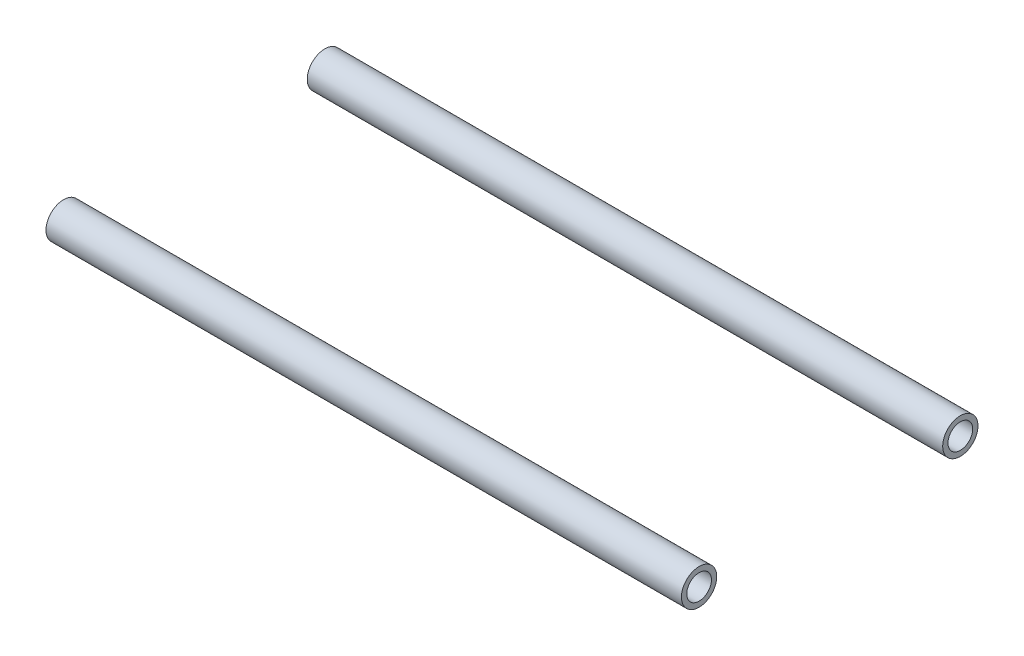
SolidWorks part; units mm, degrees
ref_plane "Front Plane" through (0, 0, 0) normal (0, 0, 1) x (1, 0, 0)
ref_plane "Top Plane" through (0, 0, 0) normal (0, 1, 0) x (1, 0, 0)
ref_plane "Right Plane" through (0, 0, 0) normal (1, 0, 0) x (0, 0, -1)
sketch "Sketch2" plane through (0, 0, 0) normal (0, 0, 1) x (1, 0, 0)
  line L0 (0, 0) -> (0, 2240) construction
  dimension "D1" = 2240
sketch "Sketch3" plane through (0, 0, 0) normal (0, 0, 1) x (1, 0, 0)
  line L0 (0, 1120) -> (2600, 1120) construction
  line L1 (0, 0) -> (0, 2240) construction
  line L2 (0, 1120) -> (1800, 1120) construction
  dimension "D1" = 2600
  dimension "D2" = 1800
ref_plane "Plane1" through (1800, 0, 0) normal (1, 0, 0) x (0, 0, -1)
ref_plane "Plane2" through (2600, 0, 0) normal (1, 0, 0) x (0, 0, -1)
sketch "Sketch6" plane through (2600, 0, 0) normal (1, 0, 0) x (0, 0, -1)
  line L0 (0, 1370) -> (0, 870) construction
  point P5 (0, 1120)
  dimension "D1" = 500
sketch "Sketch4" plane through (1800, 0, 0) normal (1, 0, 0) x (0, 0, -1)
  line L0 (0, 2240) -> (0, 0) construction
  line L1 (0, 0) -> (0, 2240) construction
  line L2 (370, 0) -> (-370, 0) construction
  line L3 (370, 2240) -> (-370, 2240) construction
  point P8 (0, 0)
  point P10 (0, 2240)
  dimension "D1" = 740
  dimension "D2" = 2240
sketch "Sketch5" plane through (0, 0, 0) normal (1, 0, 0) x (0, 0, -1)
  line L0 (-370, 2240) -> (370, 2240) construction
  line L2 (370, 0) -> (-370, 0) construction
  point P4 (0, 2240)
  point P9 (0, 0)
  dimension "D1" = 740
ref_plane "Plane3" through (0, 2240, 0) normal (0, -1, 0) x (-1, 0, 0)
ref_plane "Plane4" through (0, 0, 0) normal (0, 1, 0) x (1, 0, 0)
ref_plane "Plane5" through (458.1542, 0, 990.6037) normal (0.4198, 0, 0.9076) x (0.9076, 0, -0.4198)
ref_plane "Plane6" through (458.1542, 0, -990.6037) normal (-0.4198, 0, 0.9076) x (0.9076, 0, 0.4198)
sketch "Sketch7" plane through (0, 2240, 0) normal (0, -1, 0) x (-1, 0, 0)
  line L0 (-1800, -370) -> (0, -370)
  line L1 (-1800, 370) -> (-1800, -370) construction
  line L2 (0, -370) -> (0, 370) construction
  line L3 (0, 370) -> (0, -370) construction
  line L4 (-1800, 370) -> (0, 370)
  line L5 (-1800, 456.5) -> (-1800, -456.5) construction
sketch "Sketch8" plane through (0, 0, 0) normal (0, 1, 0) x (1, 0, 0)
  line L0 (1800, -370) -> (0, -370)
  line L1 (1800, 370) -> (0, 370)
sketch "Sketch9" plane through (458.1542, 0, -990.6037) normal (-0.4198, 0, 0.9076) x (0.9076, 0, 0.4198)
  line L0 (2359.8303, 870) -> (1478.411, 0)
  line L1 (2359.8303, 1370) -> (1478.411, 2240)
sketch "Sketch10" plane through (458.1542, 0, 990.6037) normal (0.4198, 0, 0.9076) x (0.9076, 0, -0.4198)
  line L0 (1478.411, 0) -> (2359.8303, 870)
  line L1 (1478.411, 2240) -> (2359.8303, 1370)
  line L2 (2359.8303, 870) -> (2359.8303, 1370)
sketch "Sketch11" plane through (0, 0, 0) normal (1, 0, 0) x (0, 0, -1)
  circle A0 centre (370, 2240) radius 50
  circle A1 centre (370, 2240) radius 35
  dimension "D1" = 100
  dimension "D2" = 15
sweep "MemberTL" add profiles "Sketch11" path "Sketch7"
sketch "Sketch12" plane through (0, 0, 0) normal (1, 0, 0) x (0, 0, -1)
  circle A0 centre (-370, 2240) radius 50
  circle A1 centre (-370, 2240) radius 35
  dimension "D1" = 100
  dimension "D2" = 15
sketch "Sketch13" plane through (0, 2240, 0) normal (0, -1, 0) x (-1, 0, 0)
  line L0 (0, -370) -> (-1800, -370)
sweep "MemberTR" add profiles "Sketch12" path "Sketch13"
equation "\"hatchHoleDiameter\"= 600mm"
equation "\"hullThickness\"= 120mm"
equation "\"gasketHullInterconnectWidth\"= 100mm"
equation "\"collarThickness\"= 20mm"
equation "\"hatchTunnelLength\"=200"
equation "\"oRingDiameter\"=2"
equation "\"boltPatternRadiusInterconnect\"=500"
equation "\"interconnectBoltDiameter\"=30"
equation "\"hatchShaftDiameter\"=20"
equation "\"hatchMinima\"=50"
equation "\"hullDiameter\"=2000"
equation "\"hatchMaxima\"=180"
equation "\"bushingFlatHatch\"=15"
equation "\"hingePivotDiameter\"=20"
equation "\"handleWidth\"=250"
equation "\"handleHeight\"=160"
equation "\"handleThickness\"=25"
equation "\"FrameLength\"= 2600"
equation "\"D1@Sketch2\"=\"hullDiameter\"+\"hullThickness\"*2"
equation "\"FrameMidLength\"= 1800"
equation "\"D1@Sketch3\"=\"FrameLength\""
equation "\"D2@Sketch3\"=\"FrameMidLength\""
equation "\"D1@Sketch4\"=\"hatchHoleDiameter\"+\"collarThickness\" * 2 + \"TubeOD\""
equation "\"D2@Sketch4\"=\"hullDiameter\"+\"hullThickness\"*2"
equation "\"D1@Sketch5\"=\"hatchHoleDiameter\"+\"collarThickness\" * 2 + \"TubeOD\""
equation "\"TubeOD\"= 100"
equation "\"FrameBackFlat\"= 500"
equation "\"D1@Sketch6\"=\"FrameBackFlat\""
equation "\"D1@Sketch11\"=\"TubeOD\""
equation "\"TubeWall\"=15"
equation "\"D2@Sketch11\"=\"TubeWall\""
equation "\"D1@Sketch12\"=\"TubeOD\""
equation "\"D2@Sketch12\"=\"TubeWall\""
